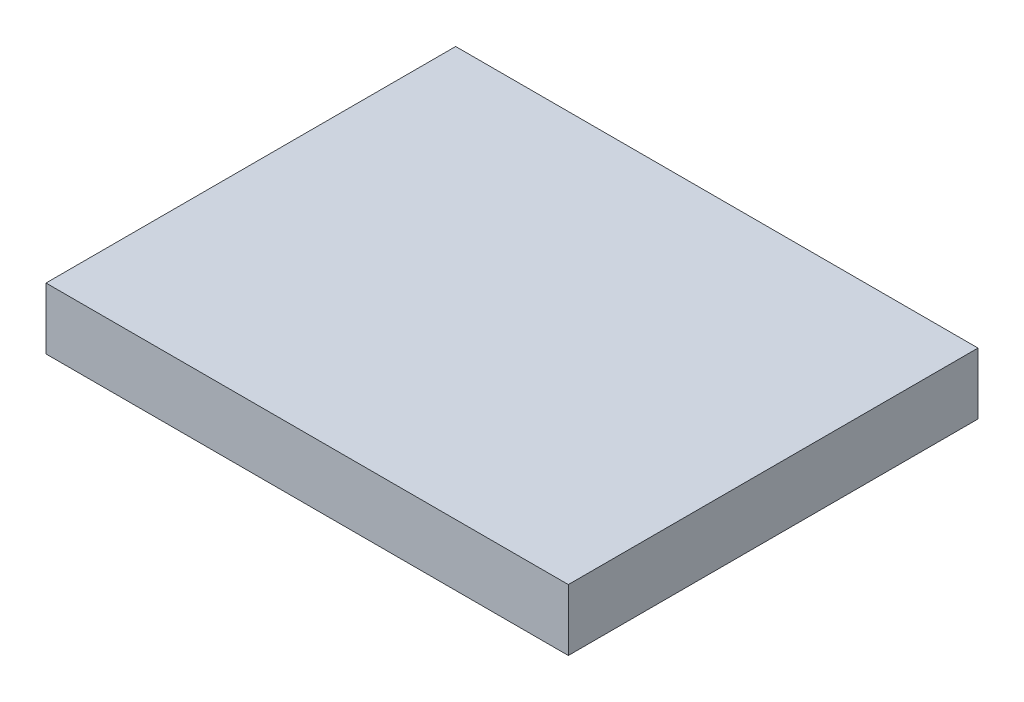
SolidWorks part; units mm, degrees
ref_plane "前视基准面" through (0, 0, 0) normal (0, 0, 1) x (1, 0, 0)
ref_plane "上视基准面" through (0, 0, 0) normal (0, 1, 0) x (1, 0, 0)
ref_plane "右视基准面" through (0, 0, 0) normal (1, 0, 0) x (0, 0, -1)
sketch "草图1" plane through (0, 0, 0) normal (0, 1, 0) x (1, 0, 0)
  line L1 (-25.5, 20) -> (25.5, 20)
  line L2 (-25.5, 20) -> (-25.5, -20)
  line L3 (-25.5, -20) -> (25.5, -20)
  line L4 (25.5, 20) -> (25.5, -20)
  line L5 (-25.5, 20) -> (25.5, -20) construction
  line L6 (-25.5, -20) -> (25.5, 20) construction
  point P0 (0, 0)
  dimension "D1" = 51
  dimension "D2" = 40
extrude "凸台-拉伸1" add sketch "草图1" along normal blind 6
